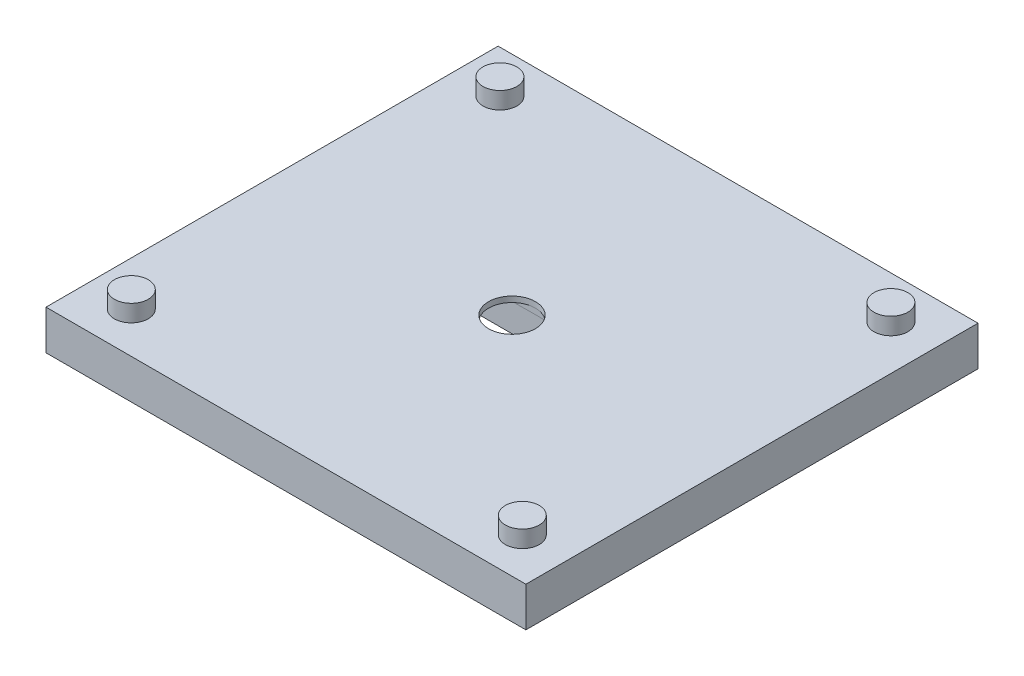
SolidWorks part; units mm, degrees
ref_plane "前视基准面" through (0, 0, 0) normal (0, 0, 1) x (1, 0, 0)
ref_plane "上视基准面" through (0, 0, 0) normal (0, 1, 0) x (1, 0, 0)
ref_plane "右视基准面" through (0, 0, 0) normal (1, 0, 0) x (0, 0, -1)
other "Configuration Table"
sketch "草图4" plane through (0, 0, 0) normal (0, 1, 0) x (1, 0, 0)
  line L0 (-44.4257, -18.1171) -> (-44.4257, -98.1171)
  line L1 (-44.4257, -18.1171) -> (40.4907, -18.1171)
  line L2 (-44.4257, -98.1171) -> (40.4907, -98.1171)
  line L3 (40.4907, -18.1171) -> (40.4907, -98.1171)
  circle A0 centre (-36.5851, -25.6363) radius 3
  circle A1 centre (32.6016, -25.6363) radius 3
  circle A2 centre (-36.5851, -90.862) radius 3
  circle A3 centre (32.6016, -90.862) radius 3
extrude "凸台-拉伸1" add sketch "草图4" along normal blind 7
sketch "草图5" plane through (0, 7, 0) normal (0, 1, 0) x (1, 0, 0)
  circle A0 centre (-36.5851, -25.6363) radius 3
  circle A1 centre (32.6016, -25.6363) radius 3
  circle A2 centre (-36.5851, -90.862) radius 3
  circle A3 centre (32.6016, -90.862) radius 3
extrude "凸台-拉伸2" add sketch "草图5" along normal blind 3 and the other way blind 7
sketch "草图6" plane through (0, 0, 0) normal (0, -1, 0) x (1, 0, 0)
  line L0 (-44.4257, 58.1171) -> (40.4907, 58.1171)
  line L1 (-44.4257, 18.1171) -> (-44.4257, 98.1171) construction
  line L2 (40.4907, 98.1171) -> (40.4907, 18.1171) construction
  line L4 (-40.9675, 53.9671) -> (37.0325, 53.9671)
  line L5 (-40.9675, 53.9671) -> (-40.9675, 62.2671)
  line L6 (-40.9675, 62.2671) -> (37.0325, 62.2671)
  line L7 (37.0325, 53.9671) -> (37.0325, 62.2671)
  line L8 (-40.9675, 53.9671) -> (37.0325, 62.2671) construction
  line L9 (-40.9675, 62.2671) -> (37.0325, 53.9671) construction
  point P6 (-1.9675, 58.1171)
extrude "切除-拉伸1" cut sketch "草图6" against normal blind 5 contours L0 L7 L6 L5 | L4 L7 L0 L5
sketch "草图7" plane through (0, 5, 0) normal (0, -1, 0) x (1, 0, 0)
  line L0 (-40.9675, 58.1171) -> (37.0325, 58.1171)
  line L1 (-40.9675, 53.9671) -> (-40.9675, 62.2671) construction
  line L2 (37.0325, 53.9671) -> (37.0325, 62.2671) construction
  line L3 (-40.9675, 62.2671) -> (37.0325, 62.2671) construction
  ellipse E0 centre (-1.9675, 58.1171) end of major axis (-40.9675, 58.1171) minor radius 4.15
extrude "切除-拉伸2" cut sketch "草图7" against normal blind 1 contours L0 E0 | L0 E0
sketch "草图8" plane through (0, 6, 0) normal (0, -1, 0) x (1, 0, 0)
  circle A0 centre (-1.9675, 58.1171) radius 4.15
extrude "切除-拉伸3" cut sketch "草图8" against normal through all
